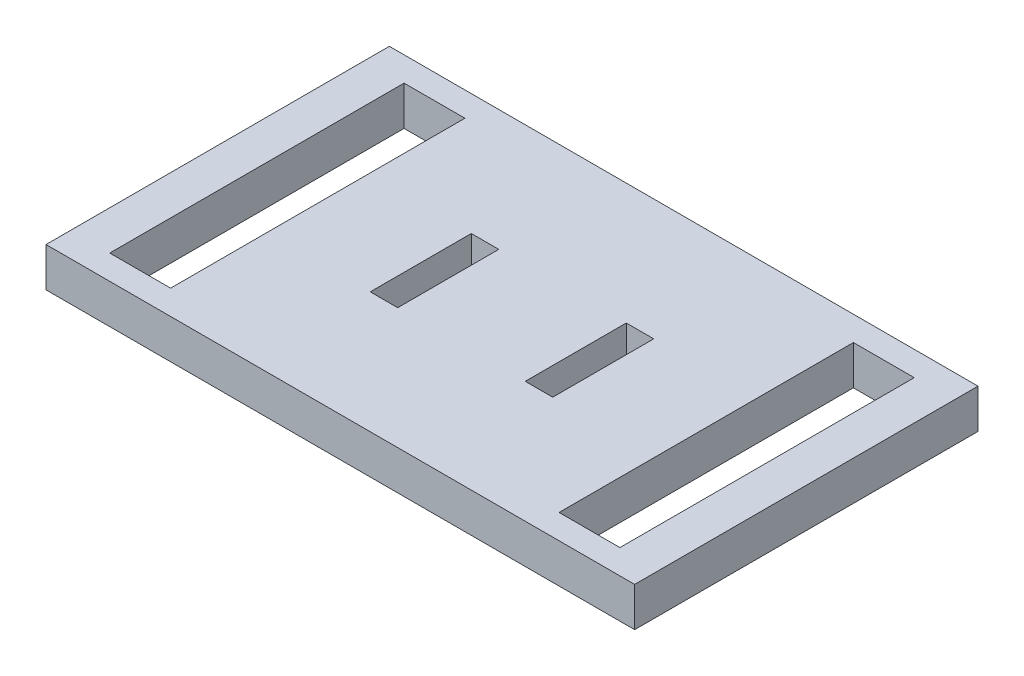
SolidWorks part; units mm, degrees
ref_plane "Front Plane" through (0, 0, 0) normal (0, 0, 1) x (1, 0, 0)
ref_plane "Top Plane" through (0, 0, 0) normal (0, 1, 0) x (1, 0, 0)
ref_plane "Right Plane" through (0, 0, 0) normal (1, 0, 0) x (0, 0, -1)
sketch "Sketch1" plane through (0, 0, 0) normal (0, 1, 0) x (1, 0, 0)
  line L0 (10.4593, 6.7522) -> (10.4593, -28.2478) construction
  line L1 (-19.5407, 6.7522) -> (40.4593, 6.7522)
  line L2 (-19.5407, 6.7522) -> (-19.5407, -28.2478)
  line L3 (-19.5407, -28.2478) -> (40.4593, -28.2478)
  line L4 (40.4593, 6.7522) -> (40.4593, -28.2478)
  line L5 (-15.5407, 4.2522) -> (-9.3407, 4.2522)
  line L6 (-15.5407, 4.2522) -> (-15.5407, -25.7478)
  line L7 (-15.5407, -25.7478) -> (-9.3407, -25.7478)
  line L8 (-9.3407, 4.2522) -> (-9.3407, -25.7478)
  line L9 (1.1593, -5.5978) -> (3.9593, -5.5978)
  line L10 (1.1593, -5.5978) -> (1.1593, -15.8978)
  line L11 (1.1593, -15.8978) -> (3.9593, -15.8978)
  line L12 (3.9593, -5.5978) -> (3.9593, -15.8978)
  line L13 (19.7593, -15.8978) -> (16.9593, -15.8978)
  line L14 (16.9593, -5.5978) -> (16.9593, -15.8978)
  line L15 (19.7593, -5.5978) -> (16.9593, -5.5978)
  line L16 (19.7593, -5.5978) -> (19.7593, -15.8978)
  line L17 (36.4593, -25.7478) -> (30.2593, -25.7478)
  line L18 (30.2593, 4.2522) -> (30.2593, -25.7478)
  line L19 (36.4593, 4.2522) -> (30.2593, 4.2522)
  line L20 (36.4593, 4.2522) -> (36.4593, -25.7478)
  dimension "D1" = 60
  dimension "D2" = 35
  dimension "D3" = 30
  dimension "D4" = 6.2
  dimension "D5" = 2.5
  dimension "D6" = 4
  dimension "D7" = 10.3
  dimension "D8" = 2.8
  dimension "D9" = 12.35
  dimension "D10" = 36.5
extrude "Boss-Extrude1" add sketch "Sketch1" along normal blind 4
